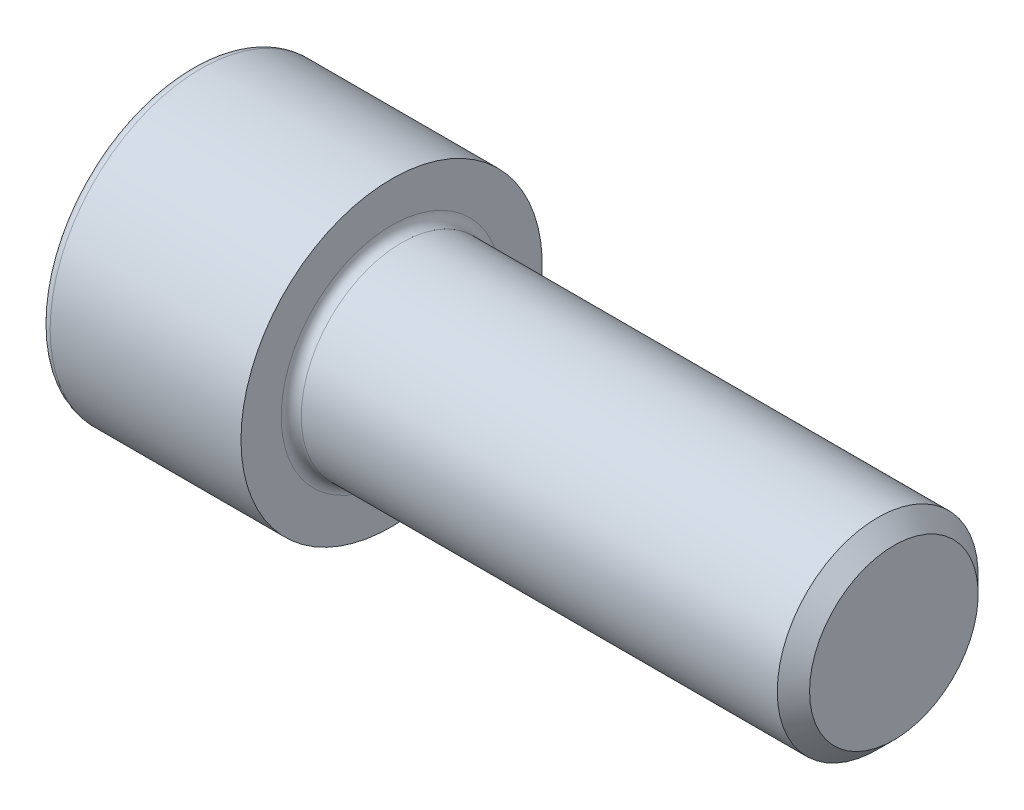
SolidWorks part; units mm, degrees
ref_plane "Plane1" through (0, 0, 0) normal (0, 0, 1) x (1, 0, 0)
ref_plane "Plane2" through (0, 0, 0) normal (0, 1, 0) x (1, 0, 0)
ref_plane "Plane3" through (0, 0, 0) normal (1, 0, 0) x (0, 0, -1)
sketch "BodySke" plane through (0, 0, 0) normal (0, 0, 1) x (1, 0, 0)
  line L0 (0, 0) -> (0, 9)
  line L1 (0, 9) -> (12, 9)
  line L2 (12, 9) -> (12, 6)
  line L3 (12, 6) -> (41.036, 6)
  line L4 (42, 5.036) -> (42, 0)
  line L5 (42, 0) -> (0, 0)
  line L6 (-31.75, 0) -> (127, 0) construction
  line L8 (42, 5.036) -> (41.036, 6)
  line L10 (42, -5.036) -> (41.036, -6) construction
  line L11 (13.75, 9.525) -> (13.75, 3.175) construction
  line L12 (12, 9.525) -> (12, 3.175) construction
  line L13 (-18, 9.525) -> (-18, 3.175) construction
  dimension "Diameter" = 12
  dimension "Head_ht" = 12
  dimension "Length" = 30
  dimension "Body_ch_ang" = 45
  dimension "Head_dia" = 18
  dimension "Minor_dia" = 10.072
  dimension "Advance" = 1.75
  dimension "Thread_nom" = 30
  dimension "Thread_length" = 60
revolve "Base-Revolve" add sketch "BodySke"
cosmetic thread "ThreadCosmetic" [suppressed]
fillet "Fillet1" radius 0.6 1 edges at (12, 0, 6)
fillet "Fillet2" radius 0.6 1 edges at (0, 0, 9)
sketch "Sketch2" plane through (0, 0, 0) normal (0, 0, 1) x (1, 0, 0)
  line L0 (0, 5.0575) -> (6, 5.0575)
  line L1 (6, 5.0575) -> (8.9199, 0)
  line L2 (-31.75, 0) -> (127, 0) construction
  line L3 (8.9199, 0) -> (0, 0)
  line L4 (0, 0) -> (0, 5.0575)
  line L6 (0, 0) -> (47.625, 0) construction
  dimension "D1" = 5.0575
  dimension "D2" = 60
  dimension "Depth" = 6
revolve "Hex-PreBroach" cut sketch "Sketch2" angle 360 about L6
sketch "Sketch3" plane through (0, 0, 0) normal (-1, 0, 0) x (0, 0.5, 0.866)
  line L0 (2.9199, 5.0575) -> (-2.9199, 5.0575)
  line L1 (-2.9199, 5.0575) -> (-5.8399, 0)
  line L2 (2.9199, 5.0575) -> (5.8399, 0)
  line L3 (2.9199, -5.0575) -> (5.8399, 0)
  line L4 (2.9199, -5.0575) -> (-2.9199, -5.0575)
  line L5 (-2.9199, -5.0575) -> (-5.8399, 0)
  dimension "D1" = 5.0575
  dimension "D2" = 5.0575
  dimension "Hex_size" = 10.115
extrude "Hex" cut sketch "Sketch3" against normal blind 6
sketch "ThdSchSke" plane through (0, 0, 0) normal (0, 0, 1) x (1, 0, 0)
  line L0 (17.25, -5.036) -> (16.575, -6)
  line L1 (17.25, -5.036) -> (17.925, -6)
  line L2 (17.925, -6) -> (17.925, -7.5)
  line L3 (-3.175, 0) -> (5.1513, 0) construction
  line L4 (0, 8.4) -> (0, -8.4) construction
  line L5 (17.925, -7.5) -> (16.575, -7.5)
  line L6 (16.575, -7.5) -> (16.575, -6)
  dimension "Thread_minor" = 10.072
  dimension "Diameter" = 12
  dimension "Start" = 17.25
  dimension "SideAngle" = 55
  dimension "VeeAngle" = 70
  dimension "Overcut" = 15
revolve "ThreadSchematic" [suppressed] cut sketch "ThdSchSke" angle 360 about L3
pattern_linear "ThdSchPat" [suppressed]
equation "\"D2@Sketch3\" = \"Hex_size@Sketch3\" / 2"
equation "\"D1@Sketch3\" = \"Hex_size@Sketch3\" / 2"
equation "\"D1@Sketch2\" = \"Hex_size@Sketch3\" / 2"
equation "\"Thread_minor@ThreadCosmetic\"  =  \"Minor_dia@BodySke\""
equation "\"Depth@Sketch2\" =  \"Key_eng@Hex\""
equation "\"Thread_length@ThreadCosmetic\" = ((sgn( (\"Length@BodySke\" - \"Advance@BodySke\" * 3.0) - \"Thread_nom@BodySke\" )-1)*( (\"Length@BodySke\" - \"Advance@BodySke\" * 3.0) - \"Thread_nom@BodySke\" ))/-2+ \"Thread_nom@BodySke\""
equation "\"Thread_minor@ThdSchSke\" = \"Minor_dia@BodySke\""
equation "\"Diameter@ThdSchSke\" = \"Diameter@BodySke\""
equation "\"Overcut@ThdSchSke\" = \"Diameter@BodySke\" * 1.25"
equation "\"Start@ThdSchSke\" = \"Head_ht@BodySke\" + \"Length@BodySke\" - \"Thread_length@ThreadCosmetic\"  '---Non-countersunk---"
equation "\"Num_threads@ThdSchPat\" = int( \"Thread_length@ThreadCosmetic\" / \"Advance@BodySke\" + 0.999 )  + 1"
equation "\"Advance@ThdSchPat\" = \"Thread_length@ThreadCosmetic\" /  (\"Num_threads@ThdSchPat\" - 1) 'relax it"
equation "\"Num_threads@ThdSchPat\" = \"Num_threads@ThdSchPat\" - sgn( \"Num_threads@ThdSchPat\" - 1) '---chamfered tips only---"
